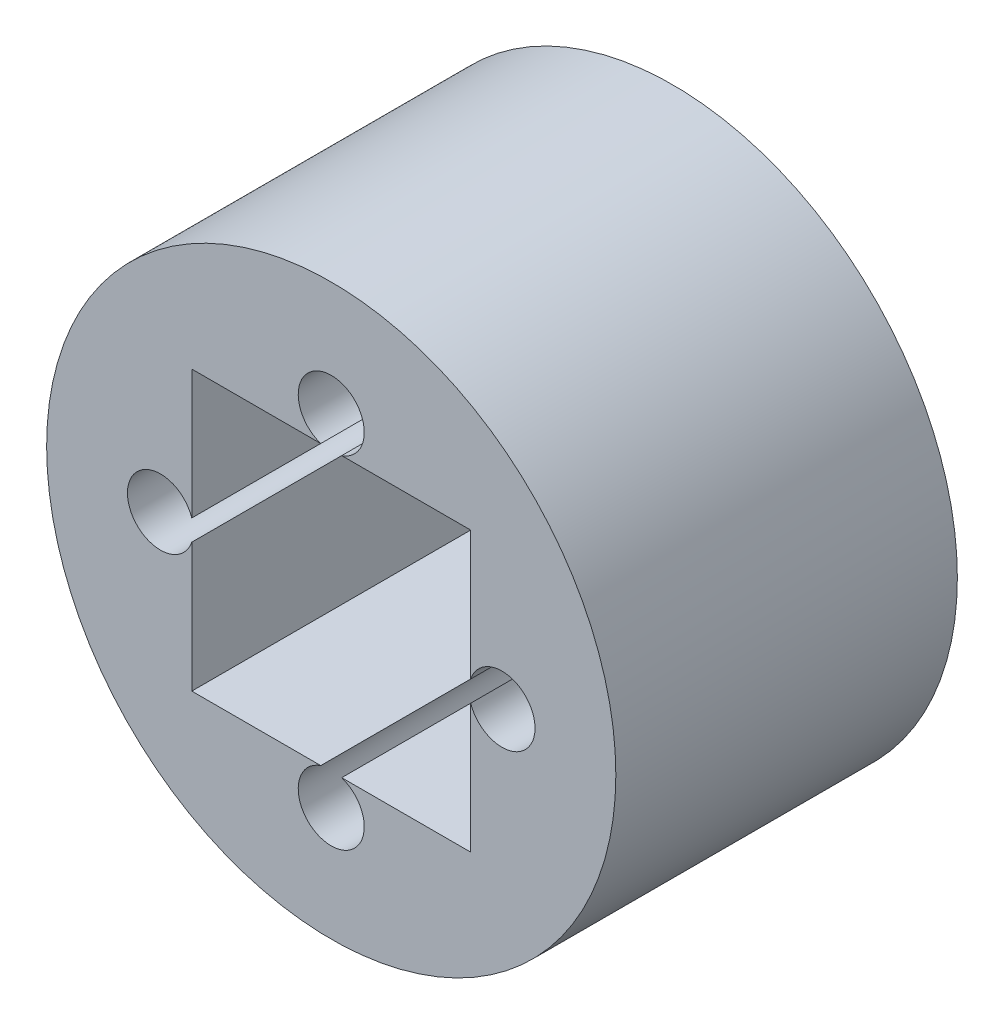
SolidWorks part; units mm, degrees
ref_plane "Front Plane" through (0, 0, 0) normal (0, 0, 1) x (1, 0, 0)
ref_plane "Top Plane" through (0, 0, 0) normal (0, 1, 0) x (1, 0, 0)
ref_plane "Right Plane" through (0, 0, 0) normal (1, 0, 0) x (0, 0, -1)
sketch "Sketch1" plane through (0, 0, 0) normal (0, 0, 1) x (1, 0, 0)
  circle A0 centre (0, 0) radius 12.5
  dimension "D2" = 25
extrude "Boss-Extrude1" add sketch "Sketch1" along normal mid plane 15
sketch "Sketch8" plane through (0, 0, 7.5) normal (0, 0, 1) x (1, 0, 0)
  line L2 (-6.125, 6.125) -> (6.125, 6.125)
  line L3 (-6.125, 6.125) -> (-6.125, -6.125)
  line L4 (-6.125, -6.125) -> (6.125, -6.125)
  line L5 (6.125, 6.125) -> (6.125, -6.125)
  line L6 (-6.125, 6.125) -> (6.125, -6.125) construction
  line L7 (-6.125, -6.125) -> (6.125, 6.125) construction
  point P5 (0, 0)
  point P14 (0, 0)
  dimension "D1" = 12.25
extrude "Cut-Extrude1" cut sketch "Sketch8" against normal up to next
sketch "Sketch11" plane through (0, 0, 7.5) normal (0, 0, 1) x (1, 0, 0)
  circle A0 centre (7.5, 0) radius 1.45
  circle A1 centre (0, -7.5) radius 1.45
  circle A2 centre (-7.5, 0) radius 1.45
  circle A3 centre (0, 7.5) radius 1.45
  point P2 (7.5, -3.1351)
  point P3 (0, 0)
  point P4 (7.5, 0)
  point P5 (7.5, 0)
  point P6 (0, 0)
  point P13 (0, 0)
  point P15 (0, 7.5)
  dimension "D1" = 2.9
  dimension "D3" = 4
extrude "Cut-Extrude4" cut sketch "Sketch11" against normal up to next
equation "\"drumDiameter\"= 25"
equation "\"drumLength\"=15"
equation "\"foamThickness\"= 5"
equation "\"drumAbove\"= 0.6"
equation "\"holderThicc\"= 2"
equation "\"D1@Boss-Extrude1\"=\"drumLength\""
equation "\"squareBarLength\"= 12.25"
equation "\"D1@Sketch8\"=\"squareBarLength\""
equation "\"toothlen\"= 2.5"
